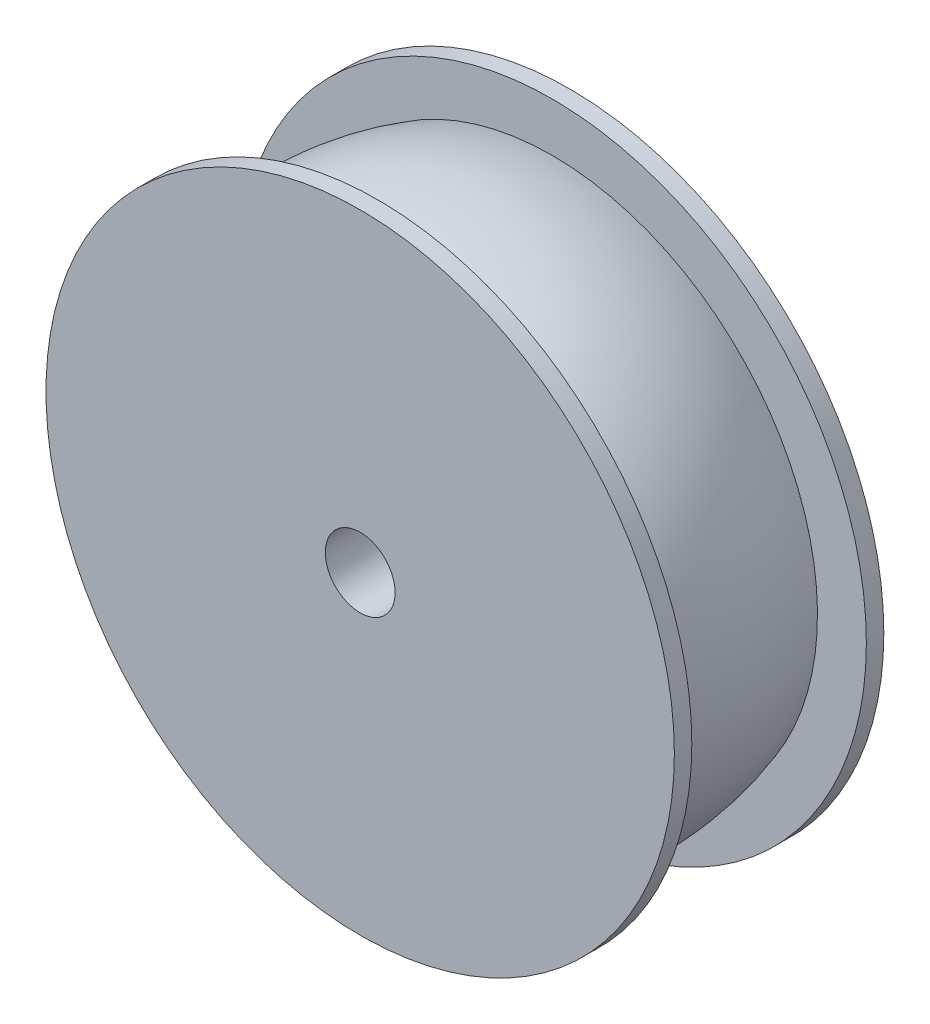
SolidWorks part; units mm, degrees
ref_plane "Front Plane" through (0, 0, 0) normal (0, 0, 1) x (1, 0, 0)
ref_plane "Top Plane" through (0, 0, 0) normal (0, 1, 0) x (1, 0, 0)
ref_plane "Right Plane" through (0, 0, 0) normal (1, 0, 0) x (0, 0, -1)
sketch "Sketch1" plane through (0, 0, 0) normal (1, 0, 0) x (0, 0, -1)
  line L0 (0, 10.6802) -> (0, -4.2008) construction
  line L1 (3, 0) -> (-3, 0)
  line L2 (-3, 0) -> (-3, 9)
  line L3 (-3, 9) -> (-2.5, 9)
  line L4 (-2.5, 9) -> (-2.5, 8)
  line L5 (3, 0) -> (3, 9)
  line L6 (-2.5, 8) -> (-2.5, 7.5993)
  line L7 (3, 9) -> (2.5, 9)
  line L8 (2.5, 9) -> (2.5, 8)
  line L9 (2.5, 7.5993) -> (2.5, 8)
  arc A0 (2.5, 7.5993) -> (-2.5, 7.5993) centre (0, 0) ccw
  point P5 (-2.5, 8.5)
  dimension "D1" = 2.5
  dimension "D2" = 3
  dimension "D4" = 9
sketch "Sketch2" plane through (0, 0, 0) normal (0, 0, 1) x (1, 0, 0)
  line L0 (-5.7682, 0) -> (5.6428, 0)
sketch "Sketch3" plane through (0, 0, 0) normal (1, 0, 0) x (0, 0, -1)
  line L0 (-8.0253, 0) -> (9.8436, 0)
sketch "Sketch4" plane through (0, 0, 0) normal (1, 0, 0) x (0, 0, -1)
  line L0 (0, 9.2744) -> (0, -5.0834)
  line L1 (0, 10.6802) -> (0, -4.2008) construction
revolve "Revolve1" add sketch "Sketch1" angle 360 about L0
ref_plane "Plane2" through (0, 0, 3) normal (0, 0, 1) x (1, 0, 0)
sketch "Sketch5" plane through (0, 0, 3) normal (0, 0, 1) x (1, 0, 0)
  circle A0 centre (0, 0) radius 1
  dimension "D1" = 2
extrude "Cut-Extrude1" cut sketch "Sketch5" against normal through all contours A0
